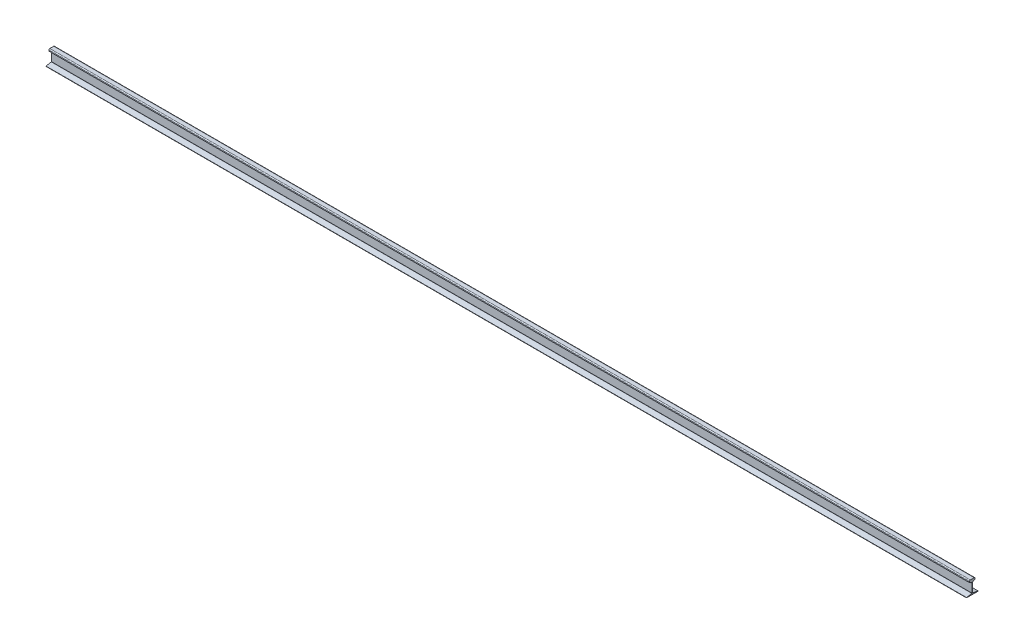
SolidWorks part; units mm, degrees
material "6061-T6 (SS)"
ref_plane "Front Plane" through (0, 0, 0) normal (0, 0, 1) x (1, 0, 0)
ref_plane "Top Plane" through (0, 0, 0) normal (0, 1, 0) x (1, 0, 0)
ref_plane "Right Plane" through (0, 0, 0) normal (1, 0, 0) x (0, 0, -1)
sketch "Sketch1" plane through (0, 0, 0) normal (1, 0, 0) x (0, 0, -1)
  line L0 (9.525, 0) -> (-9.525, 0)
  line L1 (-9.525, 0) -> (-9.525, 0.508)
  line L2 (-9.525, 0.508) -> (-0.7157, 2.1419)
  line L3 (-0.508, 2.3917) -> (-0.508, 16.1426)
  line L4 (0, 22.6314) -> (0, 0) construction
  line L5 (-2.1672, 18.525) -> (-4.6863, 19.4564)
  line L6 (-4.6863, 19.4564) -> (-4.6863, 21.1074)
  line L7 (-3.1623, 22.6314) -> (3.1623, 22.6314)
  line L8 (9.525, 0) -> (9.525, 0.508)
  line L9 (9.525, 0.508) -> (0.7157, 2.1419)
  line L10 (4.6863, 19.4564) -> (4.6863, 21.1074)
  line L11 (2.1672, 18.525) -> (4.6863, 19.4564)
  line L12 (0.508, 2.3917) -> (0.508, 16.1426)
  arc A0 (-0.508, 16.1426) -> (-2.1672, 18.525) centre (-3.048, 16.1426) ccw
  arc A1 (-0.508, 2.3917) -> (-0.7157, 2.1419) centre (-0.762, 2.3917) cw
  arc A2 (0.508, 2.3917) -> (0.7157, 2.1419) centre (0.762, 2.3917) ccw
  arc A3 (0.508, 16.1426) -> (2.1672, 18.525) centre (3.048, 16.1426) cw
  arc A4 (4.6863, 21.1074) -> (3.1623, 22.6314) centre (3.1623, 21.1074) ccw
  arc A5 (-3.1623, 22.6314) -> (-4.6863, 21.1074) centre (-3.1623, 21.1074) ccw
  point P25 (4.6863, 22.6314)
  point P28 (-4.6863, 22.6314)
  dimension "D4" = 2.54
  dimension "D6" = 0.254
  dimension "D11" = 1.524
  dimension "D1" = 9.525
  dimension "D2" = 22.6314
  dimension "D3" = 4.6863
  dimension "D5" = 0.508
  dimension "D7" = 0.508
  dimension "D8" = 0.7157
  dimension "D9" = 3.175
  dimension "D10" = 2.1672
extrude "Boss-Extrude1" add sketch "Sketch1" along normal blind 1524
